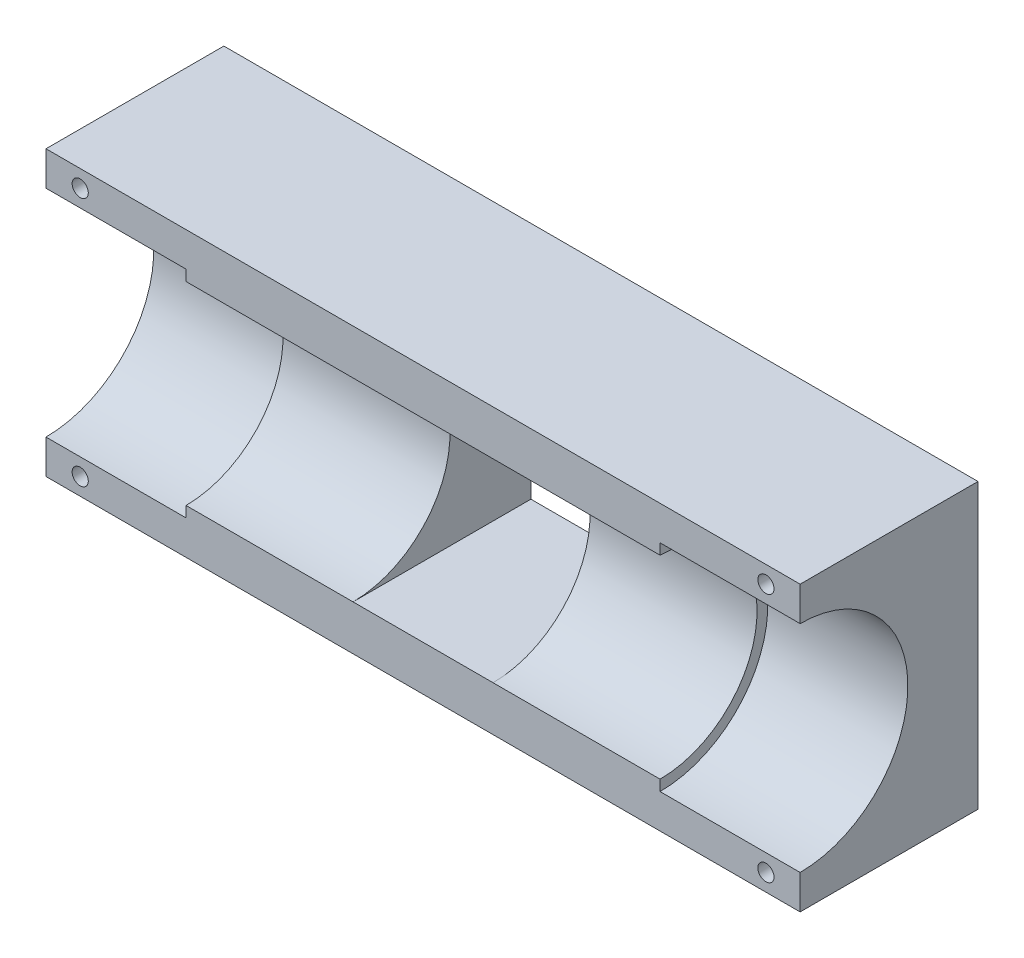
SolidWorks part; units mm, degrees
ref_plane "Front Plane" through (0, 0, 0) normal (0, 0, 1) x (1, 0, 0)
ref_plane "Top Plane" through (0, 0, 0) normal (0, 1, 0) x (1, 0, 0)
ref_plane "Right Plane" through (0, 0, 0) normal (1, 0, 0) x (0, 0, -1)
sketch "Sketch1" plane through (0, 0, 0) normal (0, 0, 1) x (1, 0, 0)
  line L1 (0, 0) -> (140, 0)
  line L2 (0, 0) -> (0, 52.7)
  line L3 (0, 52.7) -> (140, 52.7)
  line L4 (140, 0) -> (140, 52.7)
  dimension "D1" = 52.7
  dimension "D2" = 140
extrude "Boss-Extrude1" add sketch "Sketch1" along normal blind 33.02
sketch "Sketch2" plane through (0, 0, 0) normal (-1, 0, 0) x (0, 0, 1)
  line L0 (33.02, 52.7) -> (33.02, 0) construction
  line L1 (33.02, 44.35) -> (33.02, 8.35)
  arc A0 (33.02, 44.35) -> (33.02, 8.35) centre (33.02, 26.35) ccw
  dimension "D1" = 18
extrude "Cut-Extrude1" cut sketch "Sketch2" against normal through all both and the other way through all
sketch "Sketch3" plane through (0, 0, 0) normal (-1, 0, 0) x (0, 0, 1)
  line L0 (33.02, 52.7) -> (33.02, 44.35) construction
  line L1 (33.02, 8.35) -> (33.02, 0) construction
  line L2 (33.02, 46.35) -> (33.02, 6.35)
  arc A0 (33.02, 46.35) -> (33.02, 6.35) centre (33.02, 26.35) ccw
  dimension "D1" = 20
extrude "Cut-Extrude2" cut sketch "Sketch3" against normal blind 26
sketch "Sketch5" plane through (140, 0, 0) normal (1, 0, 0) x (0, 0, -1)
  line L0 (-33.02, 44.35) -> (-33.02, 52.7) construction
  line L1 (-33.02, 0) -> (-33.02, 8.35) construction
  line L2 (-33.02, 46.35) -> (-33.02, 6.35)
  arc A0 (-33.02, 46.35) -> (-33.02, 6.35) centre (-33.02, 26.35) cw
  dimension "D1" = 20
extrude "Cut-Extrude3" cut sketch "Sketch5" against normal blind 26
sketch "Sketch6" plane through (0, 0, 0) normal (0, 0, -1) x (-1, 0, 0)
  line L0 (-70, 52.7) -> (-70, 0) construction
  line L1 (-140, 52.7) -> (0, 52.7) construction
  line L2 (0, 0) -> (-140, 0) construction
  line L4 (-83, 44.35) -> (-57, 44.35)
  line L5 (-83, 44.35) -> (-83, 8.35)
  line L6 (-83, 8.35) -> (-57, 8.35)
  line L7 (-57, 44.35) -> (-57, 8.35)
  line L8 (-83, 44.35) -> (-57, 8.35) construction
  line L9 (-83, 8.35) -> (-57, 44.35) construction
  point P6 (-70, 26.35)
  dimension "D1" = 26
  dimension "D2" = 36
extrude "Cut-Extrude4" cut sketch "Sketch6" against normal through all both and the other way through all
sketch "Sketch7" plane through (0, 0, 33.02) normal (0, 0, 1) x (1, 0, 0)
  line L0 (0, 49.525) -> (140, 49.525) construction
  line L1 (0, 52.7) -> (0, 46.35) construction
  line L2 (140, 46.35) -> (140, 52.7) construction
  line L3 (0, 3.175) -> (140, 3.175) construction
  line L4 (0, 6.35) -> (0, 0) construction
  line L5 (140, 0) -> (140, 6.35) construction
  circle A0 centre (6.35, 49.525) radius 1.5
  circle A1 centre (6.35, 3.175) radius 1.5
  circle A2 centre (133.65, 49.525) radius 1.5
  circle A3 centre (133.65, 3.175) radius 1.5
  dimension "D1" = 3
  dimension "D2" = 3
  dimension "D3" = 3
  dimension "D4" = 3
  dimension "D5" = 6.35
  dimension "D6" = 6.35
  dimension "D7" = 6.35
  dimension "D8" = 6.35
extrude "Cut-Extrude5" cut sketch "Sketch7" against normal through all both and the other way through all
